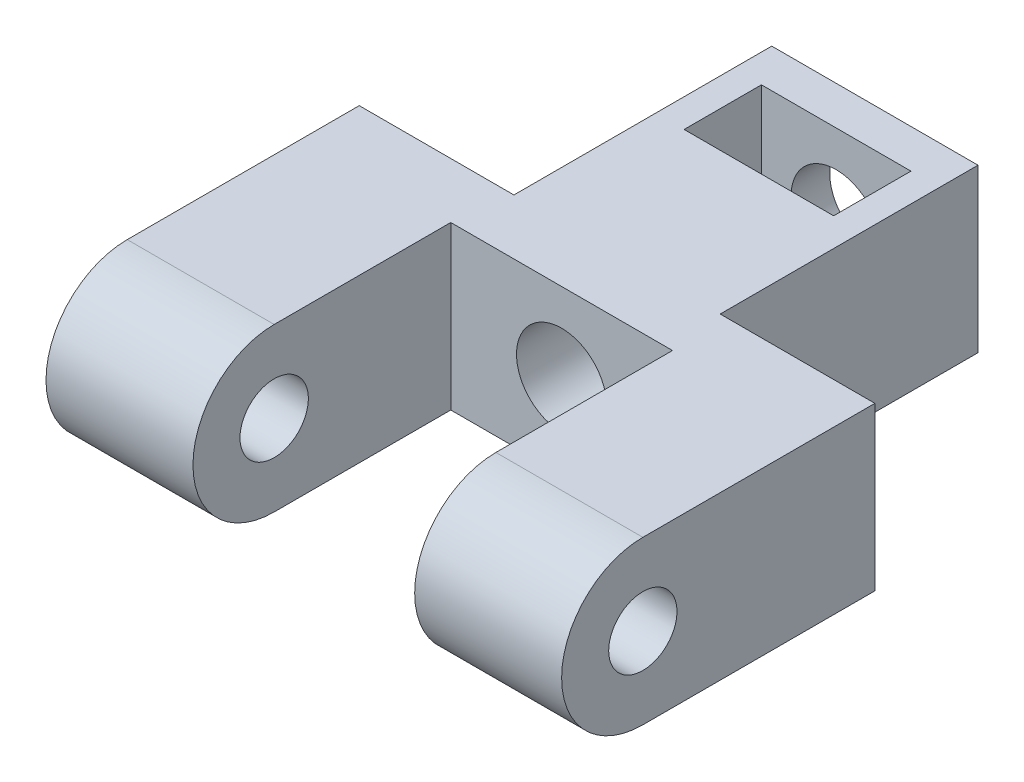
SolidWorks part; units mm, degrees
ref_plane "Front Plane" through (0, 0, 0) normal (1, 0, 0) x (0, 1, 0)
ref_plane "Top Plane" through (0, 0, 0) normal (0, 0, 1) x (0, 1, 0)
ref_plane "Right Plane" through (0, 0, 0) normal (0, 1, 0) x (-1, 0, 0)
sketch "Sketch1" plane through (0, 0, 0) normal (0, 0, 1) x (0, 1, 0)
  line L1 (-3.15, -4) -> (3.15, -4)
  line L2 (-3.15, -4) -> (-3.15, 4)
  line L3 (-3.15, 4) -> (3.15, 4)
  line L4 (3.15, -4) -> (3.15, 4)
  line L5 (-3.15, -4) -> (3.15, 4) construction
  line L6 (-3.15, 4) -> (3.15, -4) construction
  circle A0 centre (0, 0) radius 1.75
  point P0 (0, 0)
  dimension "D3" = 3.5
  dimension "D1" = 6.3
  dimension "D2" = 8
extrude "Boss-Extrude1" add sketch "Sketch1" along normal blind 10
sketch "Sketch2" plane through (0, 0, 10) normal (0, 0, 1) x (1, 0, 0)
  line L0 (-10, -3.15) -> (10, -3.15)
  line L2 (-4, -3.15) -> (4, -3.15) construction
  line L3 (-10, 3.15) -> (10, 3.15)
  line L5 (10, 3.15) -> (10, -3.15)
  line L6 (-10, -3.15) -> (-10, 3.15)
  line L7 (4, 3.15) -> (-4, 3.15) construction
  circle A0 centre (0, 0) radius 1.75
  point P3 (0, -3.15)
  point P8 (0, 3.15)
  point P10 (0, 3.15)
  dimension "D1" = 20
extrude "Boss-Extrude2" add sketch "Sketch2" along normal blind 12.15
sketch "Sketch3" plane through (-10, 0, 0) normal (-1, 0, 0) x (0, -1, 0)
  line L0 (0, 10) -> (0, 19) construction
  line L1 (-3.15, 10) -> (3.15, 10) construction
  circle A0 centre (0, 19) radius 1.325
  point P6 (0, 0)
  dimension "D2" = 2.65
  dimension "D1" = 9
extrude "Cut-Extrude1" cut sketch "Sketch3" against normal through all contours A0
sketch "Sketch4" plane through (0, 0, 22.15) normal (0, 0, 1) x (1, 0, 0)
  line L0 (-10, -3.15) -> (10, -3.15) construction
  line L1 (-4.3, 3.15) -> (4.3, 3.15)
  line L2 (-4.3, 3.15) -> (-4.3, -3.15)
  line L3 (-4.3, -3.15) -> (4.3, -3.15)
  line L4 (4.3, 3.15) -> (4.3, -3.15)
  line L5 (-4.3, 3.15) -> (4.3, -3.15) construction
  line L6 (-4.3, -3.15) -> (4.3, 3.15) construction
  point P0 (0, 0)
  dimension "D1" = 8.6
extrude "Cut-Extrude2" cut sketch "Sketch4" against normal blind 10
sketch "Sketch11" plane through (-10, 0, 0) normal (-1, 0, 0) x (0, -1, 0)
  line L0 (-3.15, 22.15) -> (-3.15, 10) construction
  line L1 (3.15, 22.15) -> (3.15, 10) construction
  line L2 (-3.15, 19) -> (-3.15, 24.1124)
  line L3 (-3.15, 24.1124) -> (3.15, 24.1124)
  line L4 (3.15, 24.1124) -> (3.15, 19)
  arc A0 (-3.15, 19) -> (3.15, 19) centre (0, 19) cw
extrude "Cut-Extrude3" cut sketch "Sketch11" against normal through all
sketch "Sketch13" plane through (0, 3.15, 0) normal (0, 1, 0) x (-1, 0, 0)
  line L0 (0, 0) -> (0, 1.5) construction
  line L1 (-2.9, 1.5) -> (2.9, 1.5)
  line L2 (2.9, 1.5) -> (2.9, 4.5)
  line L3 (2.9, 4.5) -> (-2.9, 4.5)
  line L4 (-2.9, 4.5) -> (-2.9, 1.5)
  point P6 (0, 1.5)
  dimension "D1" = 1.5
  dimension "D2" = 5.8
  dimension "D3" = 3
extrude "Cut-Extrude4" cut sketch "Sketch13" against normal through all
